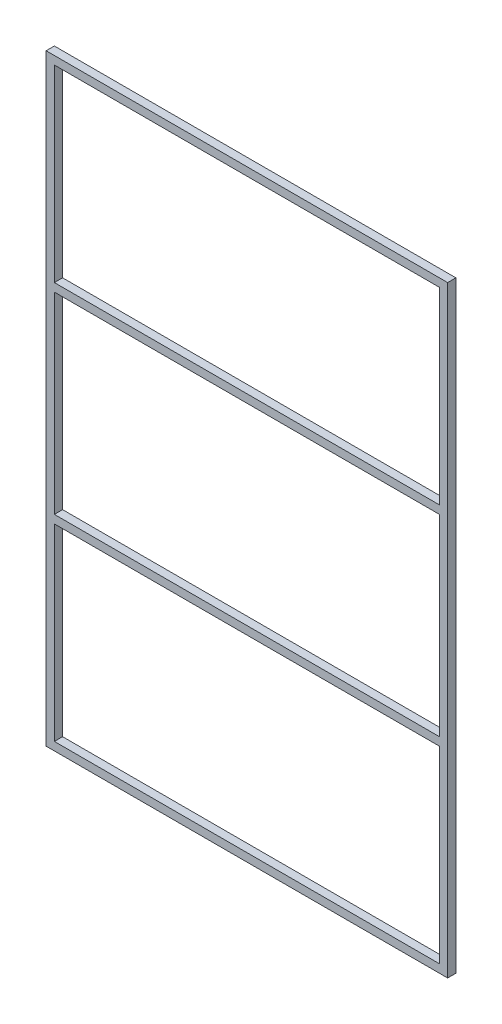
SolidWorks part; units mm, degrees
ref_plane "Front Plane" through (0, 0, 0) normal (0, 0, 1) x (1, 0, 0)
ref_plane "Top Plane" through (0, 0, 0) normal (0, 1, 0) x (1, 0, 0)
ref_plane "Right Plane" through (0, 0, 0) normal (1, 0, 0) x (0, 0, -1)
sketch "Sketch1" plane through (0, 0, 0) normal (0, 0, 1) x (1, 0, 0)
  line L1 (-1447.8313, 1201.6265) -> (992.1687, 1201.6265)
  line L2 (-1447.8313, 1201.6265) -> (-1447.8313, -2458.3735)
  line L3 (-1447.8313, -2458.3735) -> (992.1687, -2458.3735)
  line L4 (992.1687, 1201.6265) -> (992.1687, -2458.3735)
  line L5 (-1397.8313, -2408.3735) -> (942.1687, -2408.3735)
  line L7 (-1397.8313, 1151.6265) -> (942.1687, 1151.6265)
  line L9 (-1397.8313, -43.3735) -> (942.1687, -43.3735)
  line L10 (-1397.8313, -1263.3735) -> (942.1687, -1263.3735)
  line L11 (-1397.8313, -43.3735) -> (-1397.8313, -1213.3735)
  line L12 (-1397.8313, -1213.3735) -> (942.1687, -1213.3735)
  line L13 (-1397.8313, 6.6265) -> (942.1687, 6.6265)
  line L14 (942.1687, -43.3735) -> (942.1687, -1213.3735)
  line L16 (-1397.8313, 1151.6265) -> (-1397.8313, -2408.3735) construction
  line L17 (942.1687, 1151.6265) -> (942.1687, -2408.3735) construction
  line L18 (-1397.8313, 6.6265) -> (-1397.8313, 1151.6265)
  line L19 (942.1687, 6.6265) -> (942.1687, 1151.6265)
  line L20 (942.1687, -1263.3735) -> (942.1687, -2408.3735)
  line L21 (-1397.8313, -1263.3735) -> (-1397.8313, -2408.3735)
  point P17 (942.1687, -43.3735)
  point P18 (-1397.8313, 6.6265)
  point P19 (942.1687, 6.6265)
  point P20 (-1397.8313, -43.3735)
  point P21 (-1397.8313, -1213.3735)
  point P22 (-1397.8313, -1263.3735)
  point P23 (942.1687, -1213.3735)
  point P24 (942.1687, -1263.3735)
  dimension "D1" = 2440
  dimension "D2" = 3660
  dimension "D3" = 50
extrude "Boss-Extrude2" add sketch "Sketch1" along normal blind 50
